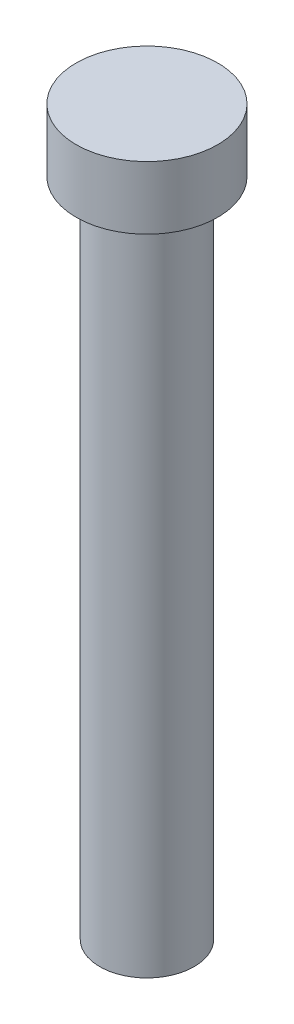
SolidWorks part; units mm, degrees
ref_plane "Front Plane" through (0, 0, 0) normal (0, 0, 1) x (1, 0, 0)
ref_plane "Top Plane" through (0, 0, 0) normal (0, 1, 0) x (1, 0, 0)
ref_plane "Right Plane" through (0, 0, 0) normal (1, 0, 0) x (0, 0, -1)
sketch "Sketch1" plane through (0, 0, 0) normal (0, 1, 0) x (1, 0, 0)
  circle A0 centre (0, 0) radius 22.5
  dimension "D1" = 45
extrude "Boss-Extrude1" add sketch "Sketch1" along normal blind 20
sketch "Sketch2" plane through (0, 0, 0) normal (0, -1, 0) x (1, 0, 0)
  circle A0 centre (0, 0) radius 15
  dimension "D1" = 30
extrude "Boss-Extrude3" add sketch "Sketch2" along normal blind 210
